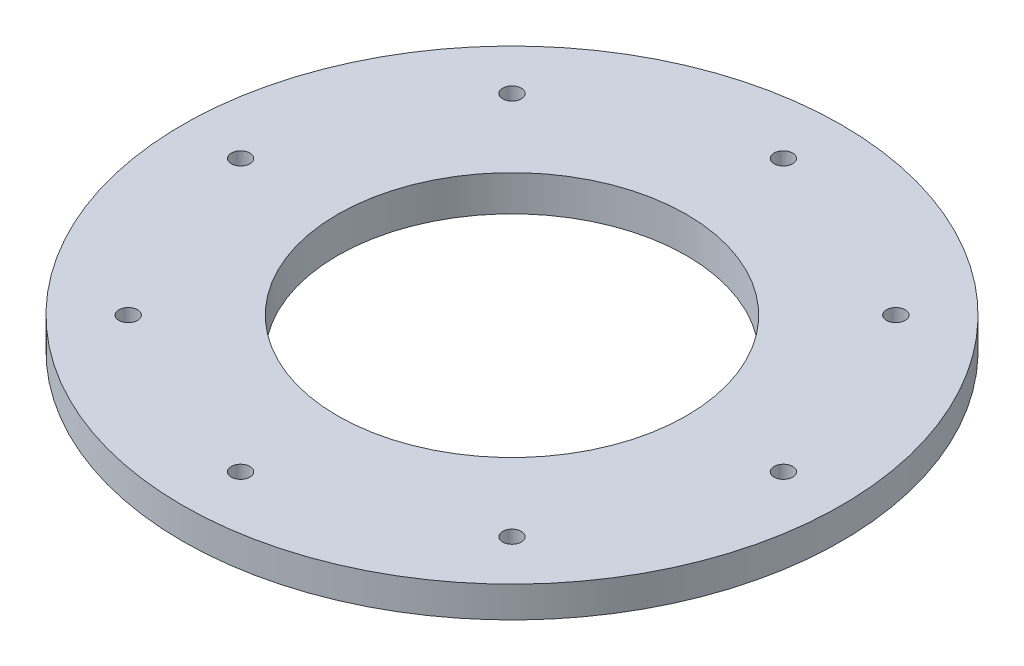
SolidWorks part; units mm, degrees
ref_plane "Front Plane" through (0, 0, 0) normal (0, 0, 1) x (1, 0, 0)
ref_plane "Top Plane" through (0, 0, 0) normal (0, 1, 0) x (1, 0, 0)
ref_plane "Right Plane" through (0, 0, 0) normal (1, 0, 0) x (0, 0, -1)
sketch "Sketch1" plane through (0, 0, 0) normal (0, 1, 0) x (1, 0, 0)
  circle A0 centre (0, 0) radius 40
  dimension "D1" = 80
extrude "Boss-Extrude1" add sketch "Sketch1" along normal blind 0.6
sketch "Sketch2" plane through (0, 0.6, 0) normal (0, 1, 0) x (1, 0, 0)
  circle A0 centre (0, 0) radius 42.5
  dimension "D1" = 85
extrude "Boss-Extrude2" add sketch "Sketch2" along normal blind 4
sketch "Sketch3" plane through (0, 0, 0) normal (0, -1, 0) x (1, 0, 0)
  circle A0 centre (0, 0) radius 22.5
  dimension "D1" = 45
extrude "Cut-Extrude1" cut sketch "Sketch3" against normal through all
sketch "Sketch4" plane through (0, 0, 0) normal (0, -1, 0) x (1, 0, 0)
  circle A0 centre (0, 35) radius 1.2
  circle A1 centre (24.7487, 24.7487) radius 1.2
  circle A2 centre (35, 0) radius 1.2
  circle A3 centre (24.7487, -24.7487) radius 1.2
  circle A4 centre (0, -35) radius 1.2
  circle A5 centre (-24.7487, -24.7487) radius 1.2
  circle A6 centre (-35, 0) radius 1.2
  circle A7 centre (-24.7487, 24.7487) radius 1.2
  point P12 (0, 0)
  dimension "D1" = 2.4
  dimension "D2" = 35
  dimension "D3" = 8
extrude "Cut-Extrude4" cut sketch "Sketch4" against normal through all
